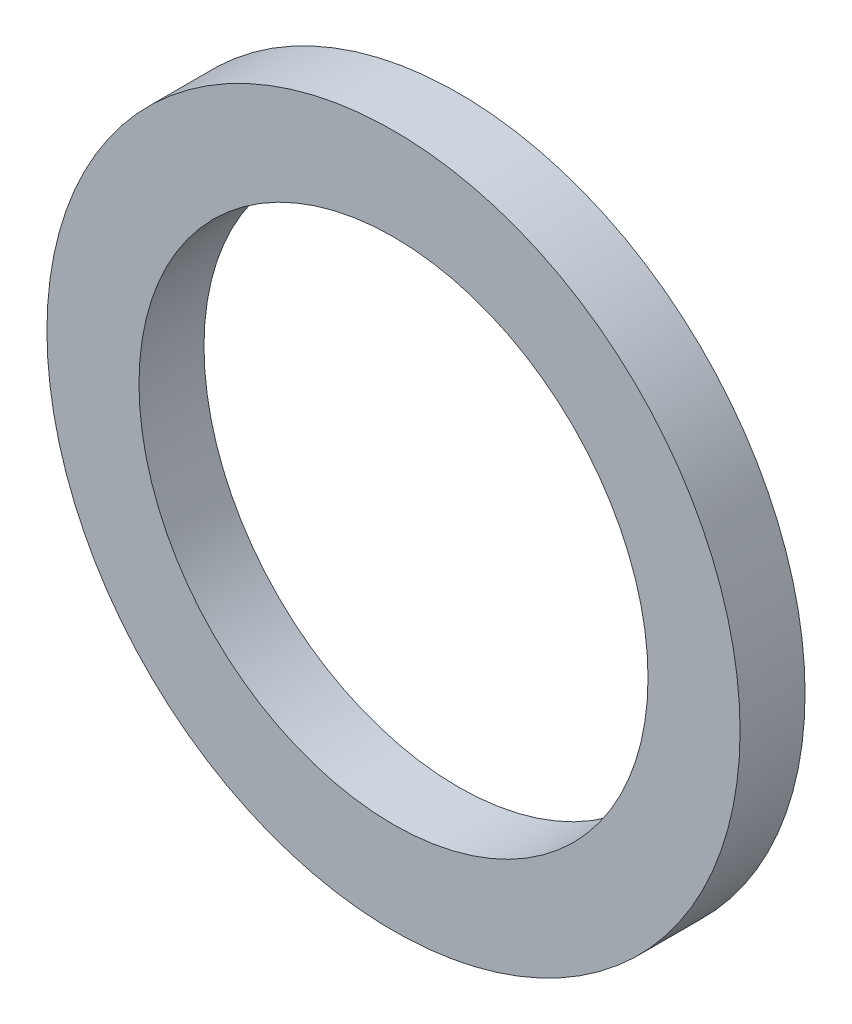
SolidWorks part; units mm, degrees
material "6061 合金"
ref_plane "Front" through (0, 0, 0) normal (0, 0, 1) x (1, 0, 0)
ref_plane "Top" through (0, 0, 0) normal (0, 1, 0) x (1, 0, 0)
ref_plane "Right" through (0, 0, 0) normal (1, 0, 0) x (0, 0, -1)
sketch "草图1" plane through (0, 0, 0) normal (0, 0, 1) x (1, 0, 0)
  circle A0 centre (0, 0) radius 2.35
  circle A1 centre (0, 0) radius 3.2
  dimension "D1" = 4.7
  dimension "D2" = 6.4
extrude "凸台-拉伸1" add sketch "草图1" along normal blind 0.6
